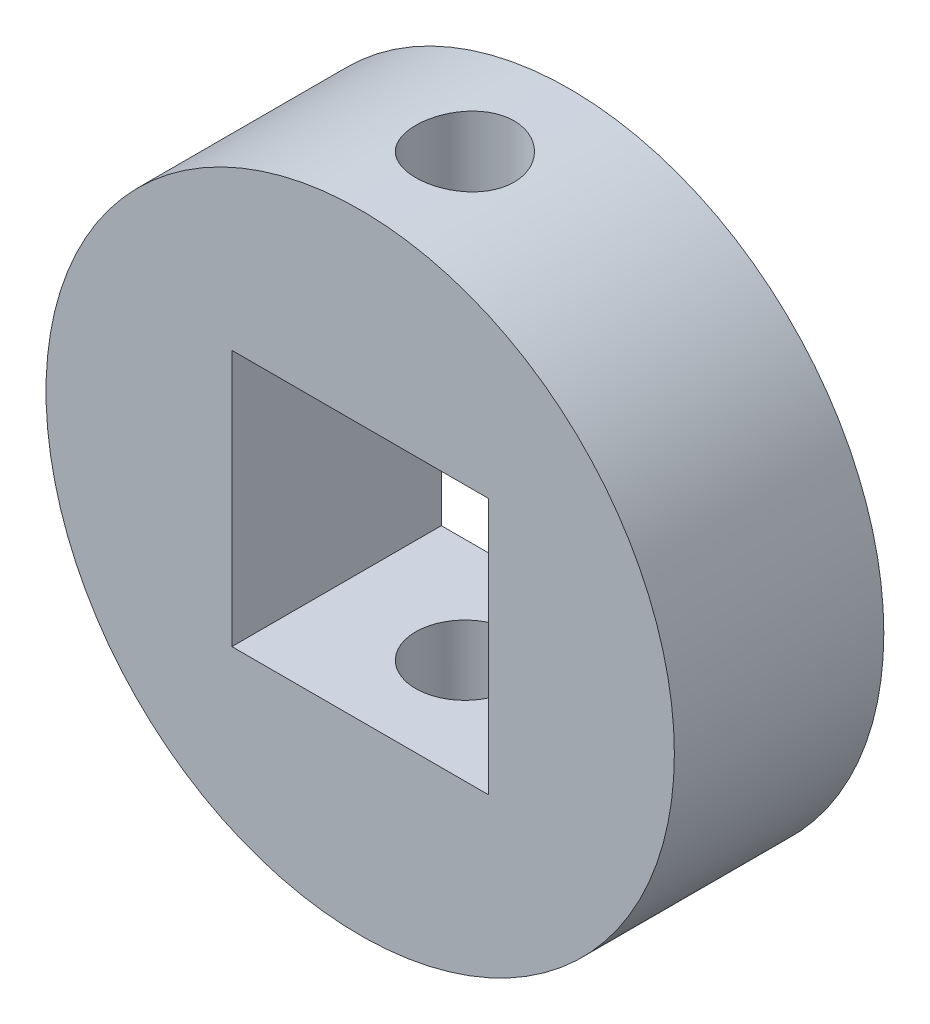
SolidWorks part; units mm, degrees
ref_plane "Plano frontal" through (0, 0, 0) normal (0, 0, 1) x (1, 0, 0)
ref_plane "Plano superior" through (0, 0, 0) normal (0, 1, 0) x (1, 0, 0)
ref_plane "Plano direito" through (0, 0, 0) normal (1, 0, 0) x (0, 0, -1)
sketch "Esboço1" plane through (0, 0, 0) normal (0, 0, 1) x (1, 0, 0)
  line L1 (6.125, 6.125) -> (-6.125, 6.125)
  line L2 (6.125, 6.125) -> (6.125, -6.125)
  line L3 (6.125, -6.125) -> (-6.125, -6.125)
  line L4 (-6.125, 6.125) -> (-6.125, -6.125)
  line L5 (6.125, 6.125) -> (-6.125, -6.125) construction
  line L6 (6.125, -6.125) -> (-6.125, 6.125) construction
  circle A0 centre (0, 0) radius 15
  dimension "D1" = 30
  dimension "D2" = 12.25
  dimension "D3" = 12.25
extrude "Ressalto-extrusão1" add sketch "Esboço1" along normal blind 10
sketch "Esboço2" plane through (0, 0, 0) normal (0, 1, 0) x (1, 0, 0)
  circle A0 centre (0, -5) radius 2.35
  dimension "D1" = 4.7
extrude "Corte-extrusão1" cut sketch "Esboço2" against normal blind 24 and the other way blind 24
